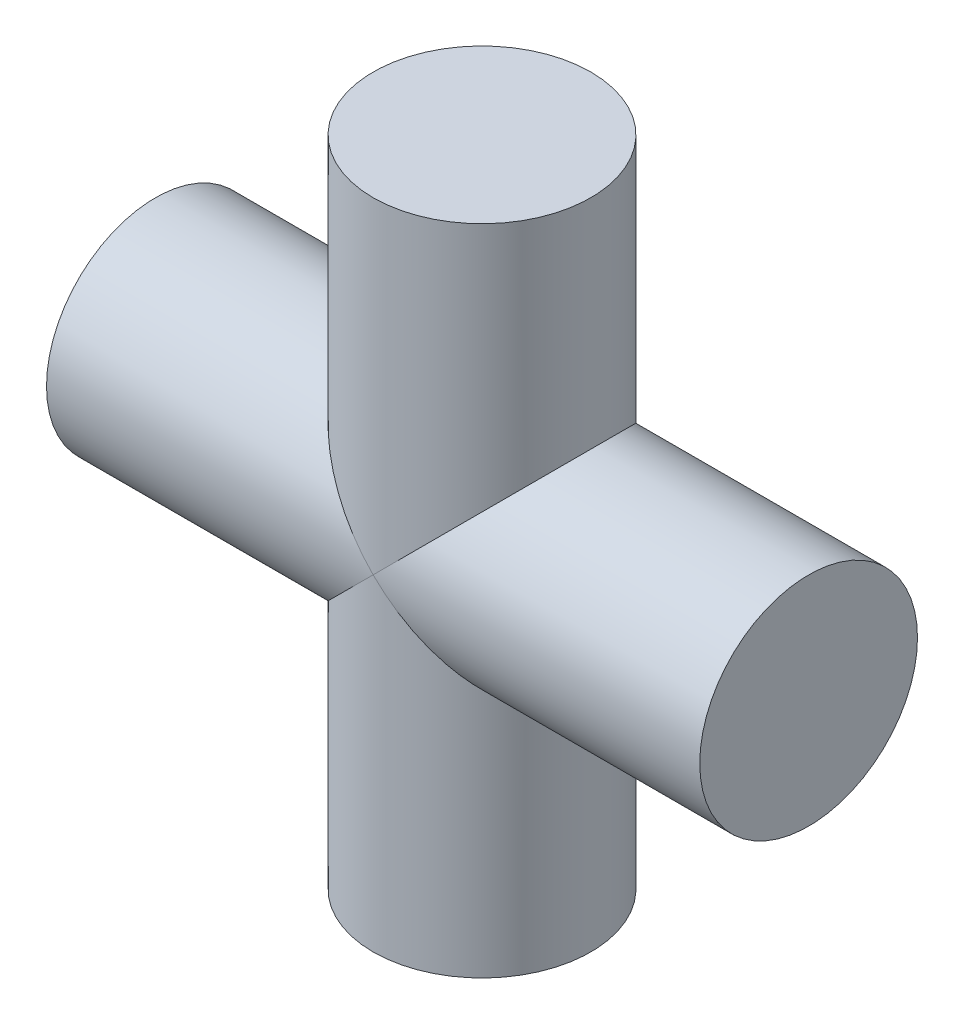
SolidWorks part; units mm, degrees
ref_plane "Front Plane" through (0, 0, 0) normal (0, 0, 1) x (1, 0, 0)
ref_plane "Top Plane" through (0, 0, 0) normal (0, 1, 0) x (1, 0, 0)
ref_plane "Right Plane" through (0, 0, 0) normal (1, 0, 0) x (0, 0, -1)
sketch "Sketch1" plane through (0, 0, 0) normal (0, 1, 0) x (1, 0, 0)
  circle A0 centre (0, 0) radius 50
  dimension "D1" = 100
extrude "Boss-Extrude1" add sketch "Sketch1" along normal mid plane 300
sketch "Sketch2" plane through (0, 0, 0) normal (1, 0, 0) x (0, 0, -1)
  circle A0 centre (0, 0) radius 50
extrude "Boss-Extrude2" add sketch "Sketch2" along normal mid plane 300
